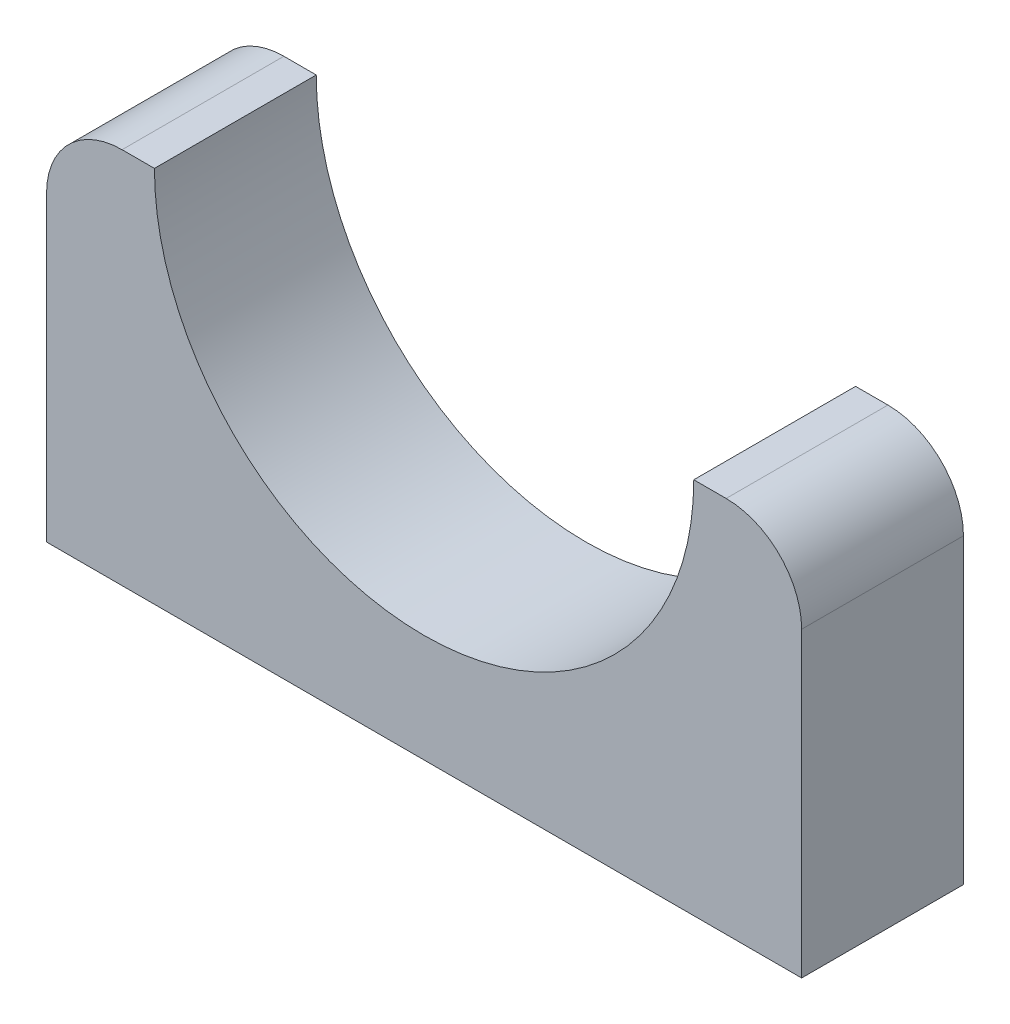
SolidWorks part; units mm, degrees
ref_plane "Front Plane" through (0, 0, 0) normal (0, 0, 1) x (1, 0, 0)
ref_plane "Top Plane" through (0, 0, 0) normal (0, 1, 0) x (1, 0, 0)
ref_plane "Right Plane" through (0, 0, 0) normal (1, 0, 0) x (0, 0, -1)
sketch "Sketch1" plane through (0, 0, 0) normal (0, 0, 1) x (1, 0, 0)
  line L0 (-17.5, 0) -> (17.5, 0)
  line L1 (17.5, 0) -> (17.5, 17.5)
  line L2 (17.5, 17.5) -> (12.5, 17.5)
  line L3 (-17.5, 0) -> (-17.5, 17.5)
  line L4 (-17.5, 17.5) -> (-12.5, 17.5)
  arc A0 (-12.5, 17.5) -> (12.5, 17.5) centre (0, 17.5) ccw
  point P4 (0, 0)
  point P11 (0, 5)
  dimension "D1" = 25
  dimension "D2" = 5
  dimension "D3" = 5
extrude "Boss-Extrude1" add sketch "Sketch1" along normal blind 7.5
fillet "Fillet1" radius 3.5 2 edges at (17.5, 17.5, 3.75) (-17.5, 17.5, 3.75)
